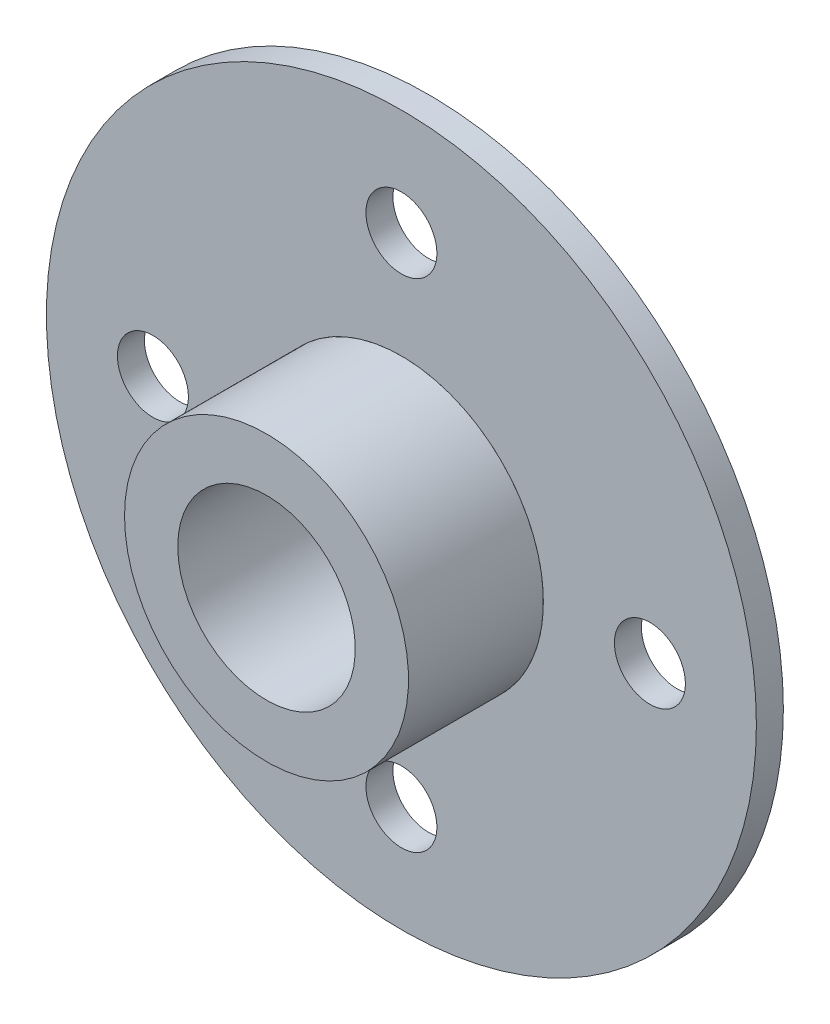
SolidWorks part; units mm, degrees
ref_plane "Ön Düzlem" through (0, 0, 0) normal (0, 0, 1) x (1, 0, 0)
ref_plane "Üst Düzlem" through (0, 0, 0) normal (0, 1, 0) x (1, 0, 0)
ref_plane "Sağ Düzlem" through (0, 0, 0) normal (1, 0, 0) x (0, 0, -1)
sketch "Çizim1" plane through (0, 0, 0) normal (0, 0, 1) x (1, 0, 0)
  circle A0 centre (0, 0) radius 10
  circle A1 centre (0, 0) radius 4
  dimension "D1" = 20
  dimension "D2" = 8
extrude "Yükseklik-Ekstrüzyon1" add sketch "Çizim1" along normal blind 0.76
sketch "Çizim2" plane through (0, 0, 0.76) normal (0, 0, 1) x (1, 0, 0)
  circle A0 centre (-7, 0) radius 1
  circle A1 centre (0, 7) radius 1
  circle A2 centre (7, 0) radius 1
  circle A3 centre (0, -7) radius 1
  point P12 (0, 0)
  dimension "D2" = 2
  dimension "D1" = 7
  dimension "D3" = 4
extrude "Kes-Ekstrüzyon1" cut sketch "Çizim2" against normal blind 0.76
sketch "Çizim3" plane through (0, 0, 0.76) normal (0, 0, 1) x (1, 0, 0)
  circle A0 centre (0, 0) radius 2.5
  circle A1 centre (0, 0) radius 4
  dimension "D1" = 5
extrude "Yükseklik-Ekstrüzyon2" add sketch "Çizim3" along normal blind 3.8 separate body
